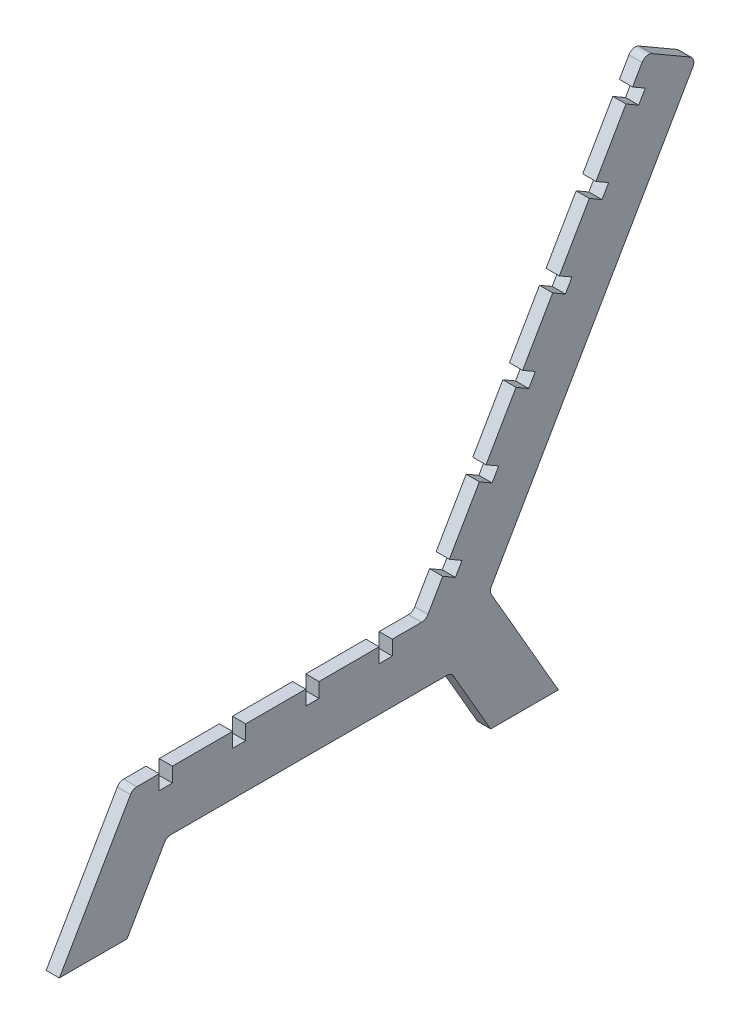
SolidWorks part; units mm, degrees
ref_plane "Piano frontale" through (0, 0, 0) normal (0, 0, 1) x (1, 0, 0)
ref_plane "Piano superiore" through (0, 0, 0) normal (0, 1, 0) x (1, 0, 0)
ref_plane "Piano destro" through (0, 0, 0) normal (1, 0, 0) x (0, 0, -1)
sketch "Schizzo1" plane through (0, 0, 0) normal (1, 0, 0) x (0, 0, -1)
  line L0 (36.2724, 0) -> (-663.7276, 0) construction
  line L1 (36.2724, 0) -> (36.2724, 700) construction
  line L2 (-109.5038, 330) -> (-127.5038, 330)
  line L3 (-9.5038, 330) -> (-27.5038, 330)
  line L4 (36.2724, 350) -> (-363.7276, 350)
  line L5 (36.2724, 350) -> (336.2724, 869.6152)
  line L6 (-363.7276, 350) -> (-463.7276, 176.7949)
  line L7 (336.2724, 869.6152) -> (405.5545, 829.6152)
  line L8 (405.5545, 829.6152) -> (122.875, 340)
  line L9 (122.875, 340) -> (217.1015, 176.7949)
  line L10 (-463.7276, 176.7949) -> (-371.3515, 176.7949)
  line L11 (-371.3515, 176.7949) -> (-317.5395, 270)
  line L12 (-317.5395, 270) -> (70.9135, 270)
  line L13 (70.9135, 270) -> (124.7254, 176.7949)
  line L14 (124.7254, 176.7949) -> (217.1015, 176.7949)
  line L15 (-9.5038, 330) -> (-9.5038, 350)
  line L16 (-9.5038, 350) -> (-27.5038, 350)
  line L17 (-27.5038, 330) -> (-27.5038, 350)
  line L18 (-109.5038, 330) -> (-109.5038, 350)
  line L19 (-109.5038, 350) -> (-127.5038, 350)
  line L20 (-127.5038, 330) -> (-127.5038, 350)
  line L21 (-209.5038, 330) -> (-227.5038, 330)
  line L22 (-209.5038, 330) -> (-209.5038, 350)
  line L23 (-209.5038, 350) -> (-227.5038, 350)
  line L24 (-227.5038, 330) -> (-227.5038, 350)
  line L25 (-309.5038, 330) -> (-327.5038, 330)
  line L26 (-309.5038, 330) -> (-309.5038, 350)
  line L27 (-309.5038, 350) -> (-327.5038, 350)
  line L28 (-327.5038, 330) -> (-327.5038, 350)
  line L29 (135.633, 482.0975) -> (126.633, 466.5091)
  line L30 (85.633, 395.495) -> (76.633, 379.9065)
  line L31 (85.633, 395.495) -> (68.3125, 405.495)
  line L32 (68.3125, 405.495) -> (59.3125, 389.9065)
  line L33 (76.633, 379.9065) -> (59.3125, 389.9065)
  line L34 (135.633, 482.0975) -> (118.3125, 492.0975)
  line L35 (118.3125, 492.0975) -> (109.3125, 476.5091)
  line L36 (126.633, 466.5091) -> (109.3125, 476.5091)
  line L37 (185.633, 568.7001) -> (176.633, 553.1116)
  line L38 (185.633, 568.7001) -> (168.3125, 578.7001)
  line L39 (168.3125, 578.7001) -> (159.3125, 563.1116)
  line L40 (176.633, 553.1116) -> (159.3125, 563.1116)
  line L41 (235.633, 655.3026) -> (226.633, 639.7141)
  line L42 (235.633, 655.3026) -> (218.3125, 665.3026)
  line L43 (218.3125, 665.3026) -> (209.3125, 649.7141)
  line L44 (226.633, 639.7141) -> (209.3125, 649.7141)
  line L45 (285.633, 741.9051) -> (276.633, 726.3167)
  line L46 (285.633, 741.9051) -> (268.3125, 751.9051)
  line L47 (268.3125, 751.9051) -> (259.3125, 736.3167)
  line L48 (276.633, 726.3167) -> (259.3125, 736.3167)
  line L49 (335.633, 828.5077) -> (326.633, 812.9192)
  line L50 (335.633, 828.5077) -> (318.3125, 838.5077)
  line L51 (318.3125, 838.5077) -> (309.3125, 822.9192)
  line L52 (326.633, 812.9192) -> (309.3125, 822.9192)
  dimension "D1" = 700
  dimension "D2" = 700
  dimension "D3" = 600
  dimension "D4" = 400
  dimension "D5" = 200
  dimension "D6" = 120
  dimension "D7" = 80
  dimension "D8" = 80
  dimension "D9" = 80
  dimension "D10" = 120
  dimension "D11" = 80
  dimension "D12" = 18
  dimension "D13" = 20
  dimension "D15" = 18
  dimension "D16" = 20
  dimension "D17" = 6
  dimension "D14" = 4
extrude "Estrusione-Estrusione1" add sketch "Schizzo1" along normal blind 18 contours L13 L14 L9 L8 L7 L5 L4 L6 L10 L11 L12
fillet "Raccordo1" radius 10 1 edges at (9, 350, -36.2724)
fillet "Raccordo2" radius 10 6 edges at (9, 829.6152, -405.5545) (9, 869.6152, -336.2724) (9, 340, -122.875) (9, 270, -70.9135) (9, 270, 317.5395) (9, 350, 363.7276)
